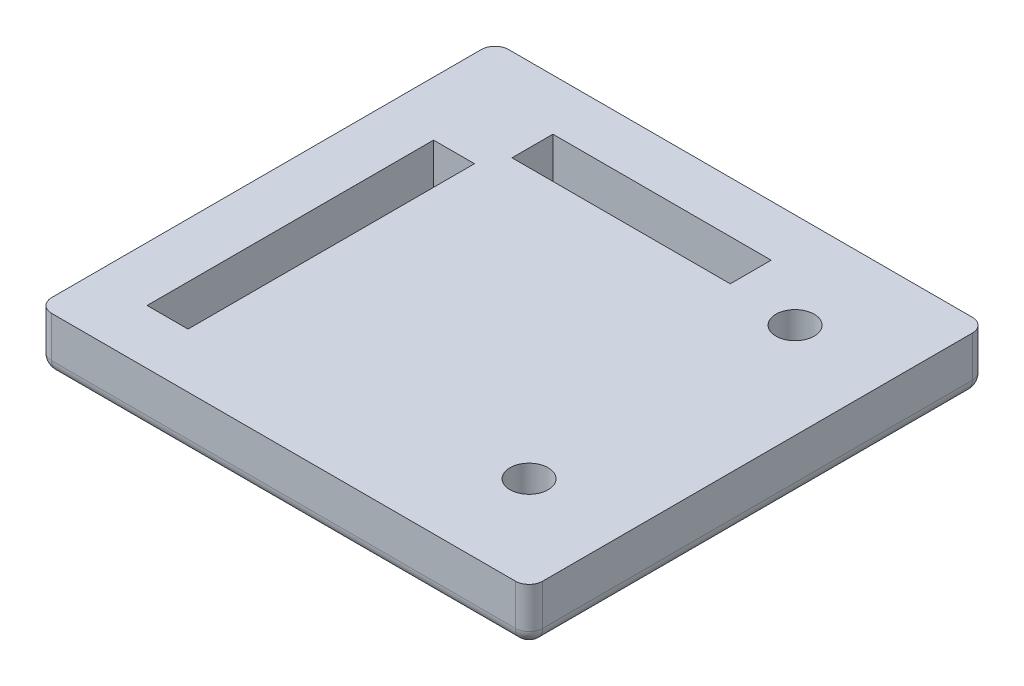
SolidWorks part; units mm, degrees
ref_plane "Front Plane" through (0, 0, 0) normal (0, 0, 1) x (1, 0, 0)
ref_plane "Top Plane" through (0, 0, 0) normal (0, 1, 0) x (1, 0, 0)
ref_plane "Right Plane" through (0, 0, 0) normal (1, 0, 0) x (0, 0, -1)
sketch "Sketch1" plane through (0, 0, 0) normal (0, 1, 0) x (1, 0, 0)
  line L1 (-18, 16.75) -> (18, 16.75)
  line L2 (-18, 16.75) -> (-18, -16.75)
  line L3 (-18, -16.75) -> (18, -16.75)
  line L4 (18, 16.75) -> (18, -16.75)
  line L5 (-18, 16.75) -> (18, -16.75) construction
  line L6 (-18, -16.75) -> (18, 16.75) construction
  line L7 (-14, 8.25) -> (-11, 8.25)
  line L8 (-14, 8.25) -> (-14, -12.75)
  line L9 (-14, -12.75) -> (-11, -12.75)
  line L10 (-11, 8.25) -> (-11, -12.75)
  line L11 (6, 13) -> (-10, 13)
  line L12 (6, 13) -> (6, 10)
  line L13 (6, 10) -> (-10, 10)
  line L14 (-10, 13) -> (-10, 10)
  circle A0 centre (11, -9.75) radius 1.4
  circle A1 centre (11, 9.75) radius 1.4
  point P0 (0, 0)
  dimension "D3" = 2.8
  dimension "D1" = 36
  dimension "D2" = 33.5
  dimension "D4" = 7
  dimension "D5" = 7
  dimension "D6" = 7
  dimension "D7" = 7
  dimension "D9" = 4
  dimension "D10" = 21
  dimension "D11" = 3
  dimension "D12" = 16
  dimension "D13" = 3
  dimension "D15" = 8
  dimension "D14" = 3.75
  dimension "D8" = 4
extrude "Base" add sketch "Sketch1" along normal blind 4
fillet "1mm Edge Fillets" radius 1 8 edges at (18, 2, 16.75) (18, 2, -16.75) (-18, 2, -16.75) (0, 0, 16.75) (18, 0, 0) (0, 0, -16.75) (-18, 0, 0) (-18, 2, 16.75)
equation "\"D5@Sketch1\"=\"D4@Sketch1\""
equation "\"D6@Sketch1\"=\"D4@Sketch1\""
equation "\"D7@Sketch1\"=\"D4@Sketch1\""
